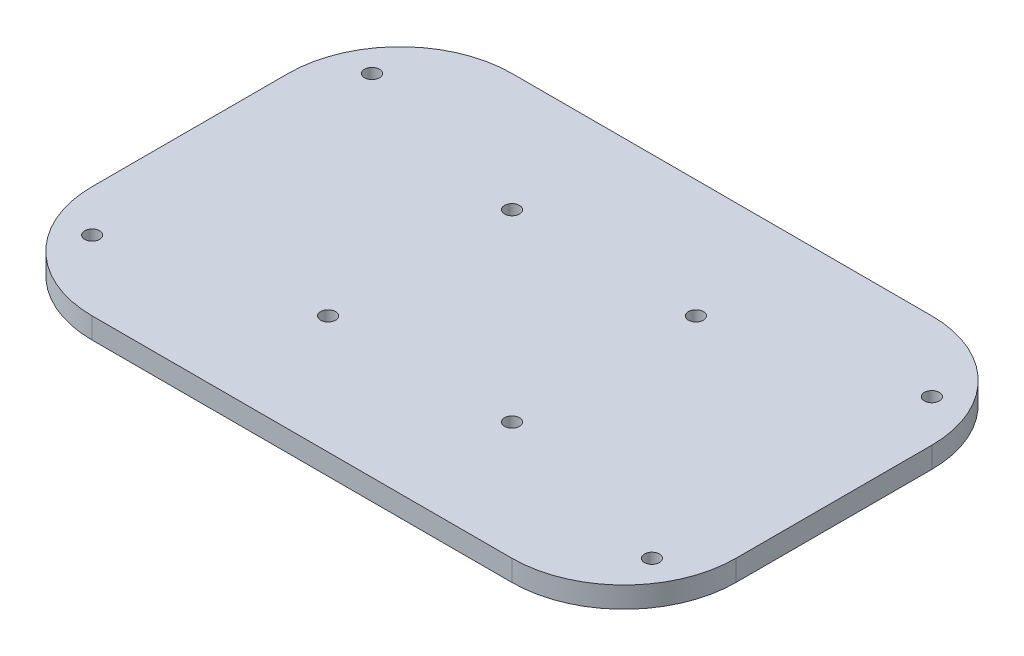
SolidWorks part; units mm, degrees
ref_plane "Front Plane" through (0, 0, 0) normal (0, 0, 1) x (1, 0, 0)
ref_plane "Top Plane" through (0, 0, 0) normal (0, 1, 0) x (1, 0, 0)
ref_plane "Right Plane" through (0, 0, 0) normal (1, 0, 0) x (0, 0, -1)
sketch "Sketch1" plane through (0, 0, 0) normal (0, 1, 0) x (1, 0, 0)
  line L1 (-47.625, -47.625) -> (47.625, -47.625)
  line L2 (-73.025, -22.225) -> (-73.025, 22.225)
  line L3 (-47.625, 47.625) -> (47.625, 47.625)
  line L4 (73.025, -22.225) -> (73.025, 22.225)
  arc A0 (47.625, -47.625) -> (73.025, -22.225) centre (47.625, -22.225) ccw
  arc A1 (-47.625, -47.625) -> (-73.025, -22.225) centre (-47.625, -22.225) cw
  arc A2 (-73.025, 22.225) -> (-47.625, 47.625) centre (-47.625, 22.225) cw
  arc A3 (47.625, 47.625) -> (73.025, 22.225) centre (47.625, 22.225) cw
  point P8 (73.025, -47.625)
  point P11 (-73.025, -47.625)
  point P16 (73.025, 47.625)
  dimension "D5" = 25.4
  dimension "D1" = 146.05
  dimension "D2" = 95.25
  dimension "D3" = 73.025
  dimension "D4" = 47.625
extrude "Boss-Extrude1" add sketch "Sketch1" along normal blind 4.7625
sketch "Sketch2" plane through (0, 4.7625, 0) normal (0, 1, 0) x (1, 0, 0)
  circle A0 centre (-63.5, -31.75) radius 1.7
  circle A1 centre (-63.5, 31.75) radius 1.7
  circle A2 centre (63.5, 31.75) radius 1.7
  circle A3 centre (63.5, -31.75) radius 1.7
  dimension "D1" = 3.4
  dimension "D2" = 3.4
  dimension "D3" = 3.4
  dimension "D4" = 3.4
  dimension "D6" = 0
  dimension "D7" = 0
  dimension "D8" = 127
  dimension "D9" = 63.5
  dimension "D10" = 0
  dimension "D5" = 0
  dimension "D11" = 63.5
  dimension "D12" = 31.75
extrude "Cut-Extrude1" cut sketch "Sketch2" against normal through all
sketch "Sketch3" plane through (0, 4.7625, 0) normal (0, 1, 0) x (1, 0, 0)
  circle A1 centre (20.8597, 20.8597) radius 1.7
  circle A2 centre (-20.8597, 20.8597) radius 1.7
  circle A3 centre (-20.8597, -20.8597) radius 1.7
  circle A4 centre (20.8597, -20.8597) radius 1.7
  dimension "D2" = 3.4
  dimension "D3" = 3.4
  dimension "D4" = 3.4
  dimension "D5" = 3.4
extrude "Cut-Extrude2" cut sketch "Sketch3" against normal through all
